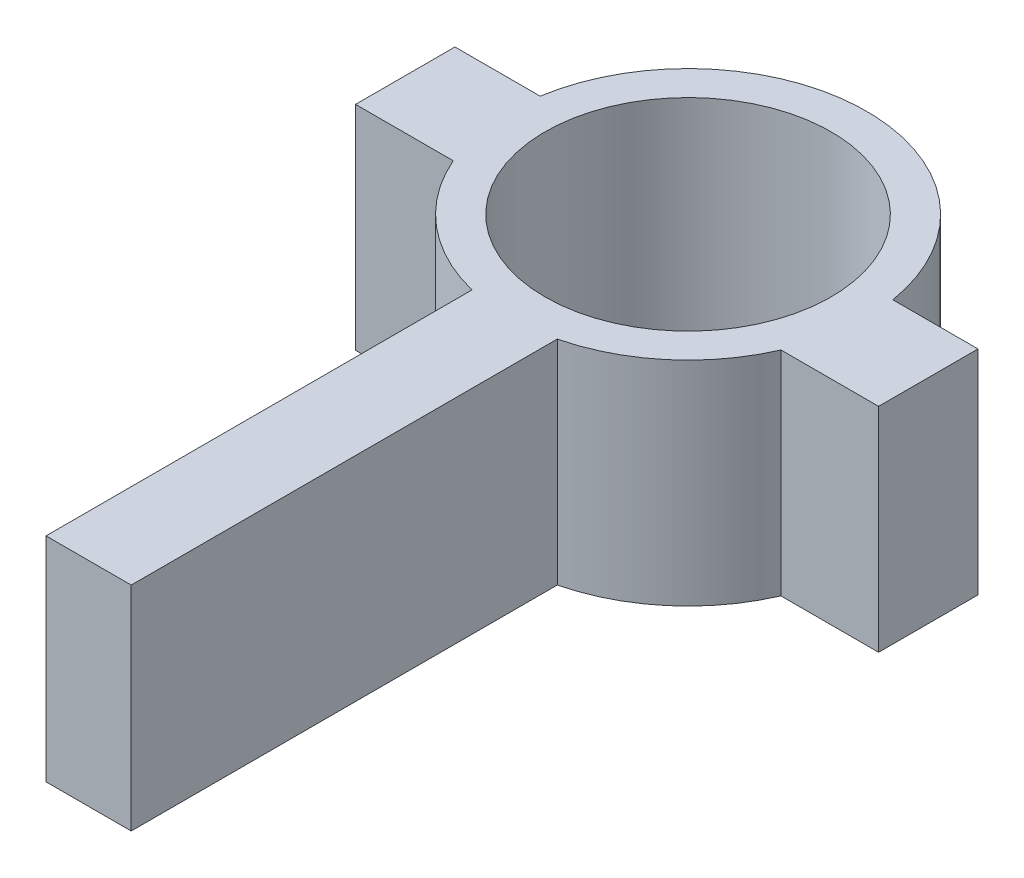
SolidWorks part; units mm, degrees
ref_plane "Front Plane" through (0, 0, 0) normal (0, 0, 1) x (1, 0, 0)
ref_plane "Top Plane" through (0, 0, 0) normal (0, 1, 0) x (1, 0, 0)
ref_plane "Right Plane" through (0, 0, 0) normal (1, 0, 0) x (0, 0, -1)
sketch "Sketch2" plane through (0, 0, 0) normal (0, 1, 0) x (1, 0, 0)
  line L0 (-36.8299, 0) -> (36.8299, 0) construction
  line L1 (-24.8299, 4) -> (-36.8299, 4)
  line L2 (-24.8299, 4) -> (-24.8299, -10)
  line L3 (-24.8299, -10) -> (-36.8299, -10)
  line L4 (-36.8299, 4) -> (-36.8299, -10)
  line L5 (-24.8299, 4) -> (-36.8299, -10) construction
  line L6 (-24.8299, -10) -> (-36.8299, 4) construction
  line L7 (24.8299, 4) -> (36.8299, 4)
  line L8 (24.8299, 4) -> (24.8299, -10)
  line L9 (24.8299, -10) -> (36.8299, -10)
  line L10 (36.8299, 4) -> (36.8299, -10)
  line L11 (24.8299, 4) -> (36.8299, -10) construction
  line L12 (24.8299, -10) -> (36.8299, 4) construction
  line L14 (-24.8299, -10) -> (24.8299, -10)
  line L15 (-24.8299, -10) -> (-24.8299, 4)
  line L16 (-24.8299, 4) -> (24.8299, 4)
  line L17 (24.8299, -10) -> (24.8299, 4)
  line L18 (-24.8299, -10) -> (24.8299, 4) construction
  line L19 (-24.8299, 4) -> (24.8299, -10) construction
  line L20 (-6, -24.4238) -> (6, -24.4238)
  line L21 (-6, -24.4238) -> (-6, -84.4238)
  line L22 (-6, -84.4238) -> (6, -84.4238)
  line L23 (6, -24.4238) -> (6, -84.4238)
  line L24 (-6, -24.4238) -> (6, -84.4238) construction
  line L25 (-6, -84.4238) -> (6, -24.4238) construction
  circle A0 centre (0, 0) radius 20.15
  circle A1 centre (0, 0) radius 25.15
  point P8 (-30.8299, -3)
  point P13 (30.8299, -3)
  point P19 (0, -3)
  point P23 (0, -54.4238)
  point P24 (0, 0)
  point P25 (0, -42.7506)
  dimension "D1" = 50.3
  dimension "D2" = 40.3
  dimension "D3" = 4
  dimension "D4" = 12
  dimension "D5" = 10
  dimension "D6" = 12
  dimension "D7" = 60
extrude "Boss-Extrude1" add sketch "Sketch2" along normal blind 30 contours A1 L15 L14 | A1 L1 L4 L3 L15 | L2 A1 | L2 A1 L14 A0 L16 | L16 A1 A0 | L14 A1 L8 L16 A0 | A1 L14 L17 | L8 A1 | A1 L17 L9 L10 L7 | L20 A1 | A1 L21 L22 L23 | L20 A1 L14 A0
